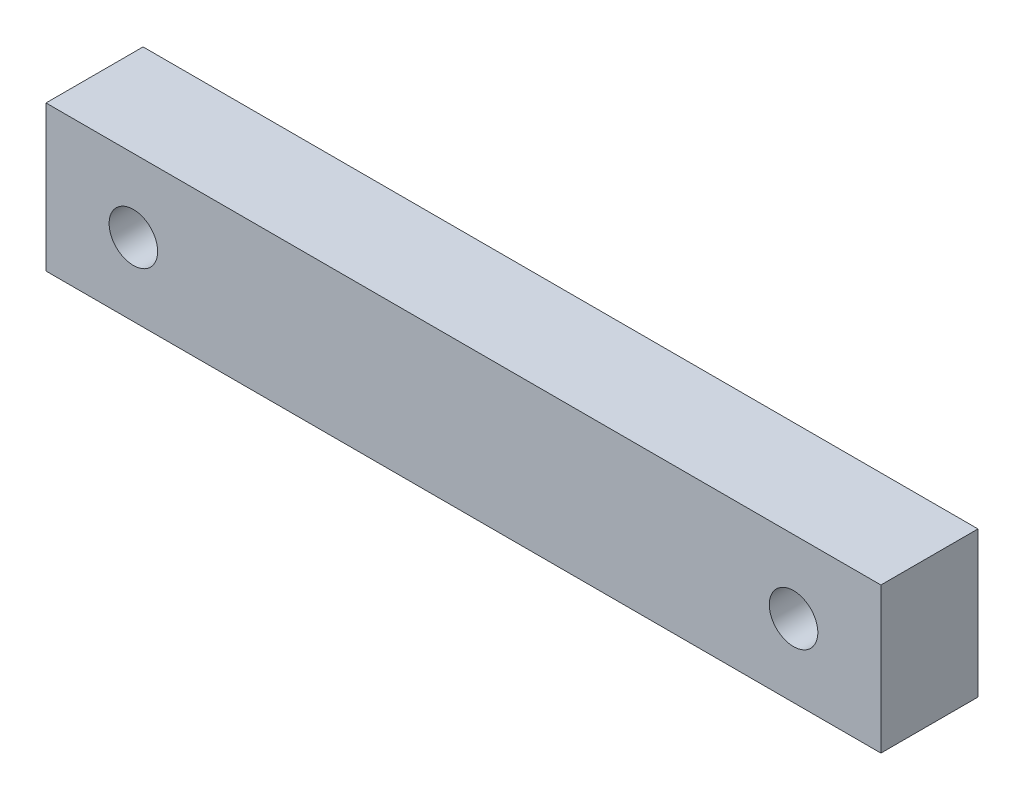
SolidWorks part; units mm, degrees
ref_plane "Front Plane" through (0, 0, 0) normal (0, 0, 1) x (1, 0, 0)
ref_plane "Top Plane" through (0, 0, 0) normal (0, 1, 0) x (1, 0, 0)
ref_plane "Right Plane" through (0, 0, 0) normal (1, 0, 0) x (0, 0, -1)
sketch "Sketch1" plane through (0, 0, 0) normal (0, 0, 1) x (1, 0, 0)
  line L0 (0, 0) -> (86, 0)
  line L1 (86, 0) -> (86, 15)
  line L2 (86, 15) -> (0, 15)
  line L3 (0, 15) -> (0, 0)
  line L4 (0, 7.5) -> (86, 7.5) construction
  line L5 (43, 15) -> (43, 0) construction
  line L6 (43, 7.5) -> (25, 7.5) construction
  line L7 (43, 7.5) -> (9, 7.5) construction
  circle A1 centre (9, 7.5) radius 2.5
  circle A3 centre (77, 7.5) radius 2.5
extrude "Boss-Extrude1" add sketch "Sketch1" along normal blind 10
